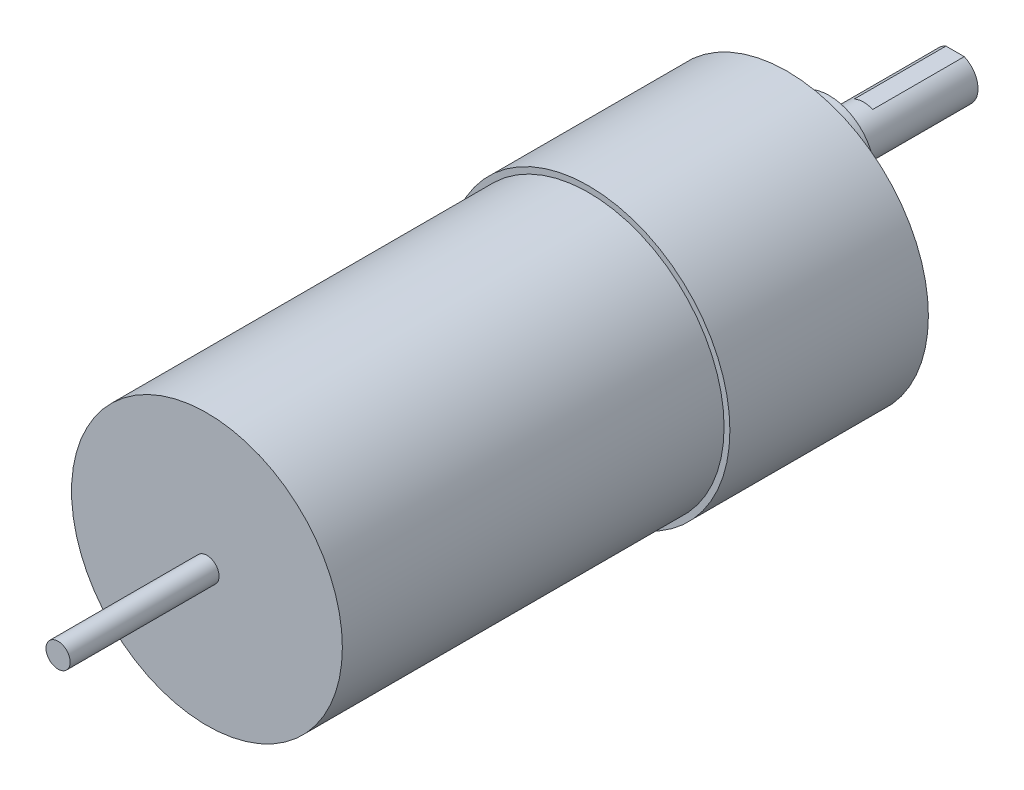
SolidWorks part; units mm, degrees
ref_plane "Front Plane" through (0, 0, 0) normal (0, 0, 1) x (1, 0, 0)
ref_plane "Top Plane" through (0, 0, 0) normal (0, 1, 0) x (1, 0, 0)
ref_plane "Right Plane" through (0, 0, 0) normal (1, 0, 0) x (0, 0, -1)
sketch "Sketch2" plane through (0, 0, 0) normal (0, 0, 1) x (1, 0, 0)
  circle A0 centre (0, 0) radius 15.5
  circle A1 centre (0, 0) radius 18.5
extrude "Boss-Extrude1" add sketch "Sketch2" along normal blind 26 contours A1
sketch "Sketch3" plane through (0, 0, 26) normal (0, 0, 1) x (1, 0, 0)
  circle A0 centre (0, 0) radius 17.7381
extrude "Boss-Extrude2" add sketch "Sketch3" along normal blind 50
sketch "Sketch4" plane through (0, 0, 76) normal (0, 0, 1) x (1, 0, 0)
  circle A0 centre (0, 0) radius 1.585
extrude "Boss-Extrude3" add sketch "Sketch4" along normal blind 19.5
sketch "Sketch5" plane through (0, 0, 0) normal (0, 0, -1) x (-1, 0, 0)
  line L0 (-31.6417, 0) -> (31.6417, 0) construction
  line L1 (0, -23.0623) -> (0, 23.0623) construction
  circle A0 centre (0, 7) radius 6
  point P4 (0, 0)
  point P8 (0, 0)
  dimension "D1" = 7
extrude "Boss-Extrude4" add sketch "Sketch5" along normal blind 5.5
sketch "Sketch6" plane through (0, 0, -5.5) normal (0, 0, -1) x (-1, 0, 0)
  circle A0 centre (0, 7) radius 3
extrude "Boss-Extrude5" add sketch "Sketch6" along normal blind 16.5
sketch "Sketch7" plane through (0, 0, -22) normal (0, 0, -1) x (-1, 0, 0)
  line L0 (-3, 7) -> (3, 7)
  line L1 (-1.199, 9.75) -> (1.199, 9.75)
  circle A0 centre (0, 7) radius 3 construction
  circle A1 centre (0, 7) radius 3 construction
  arc A3 (1.199, 9.75) -> (-1.199, 9.75) centre (0, 7) ccw
  point P12 (0, 9.75)
  circle M1 centre (0, 7) radius 3
extrude "Cut-Extrude1" cut sketch "Sketch7" against normal blind 12 and the other way through all contours L1 M1
